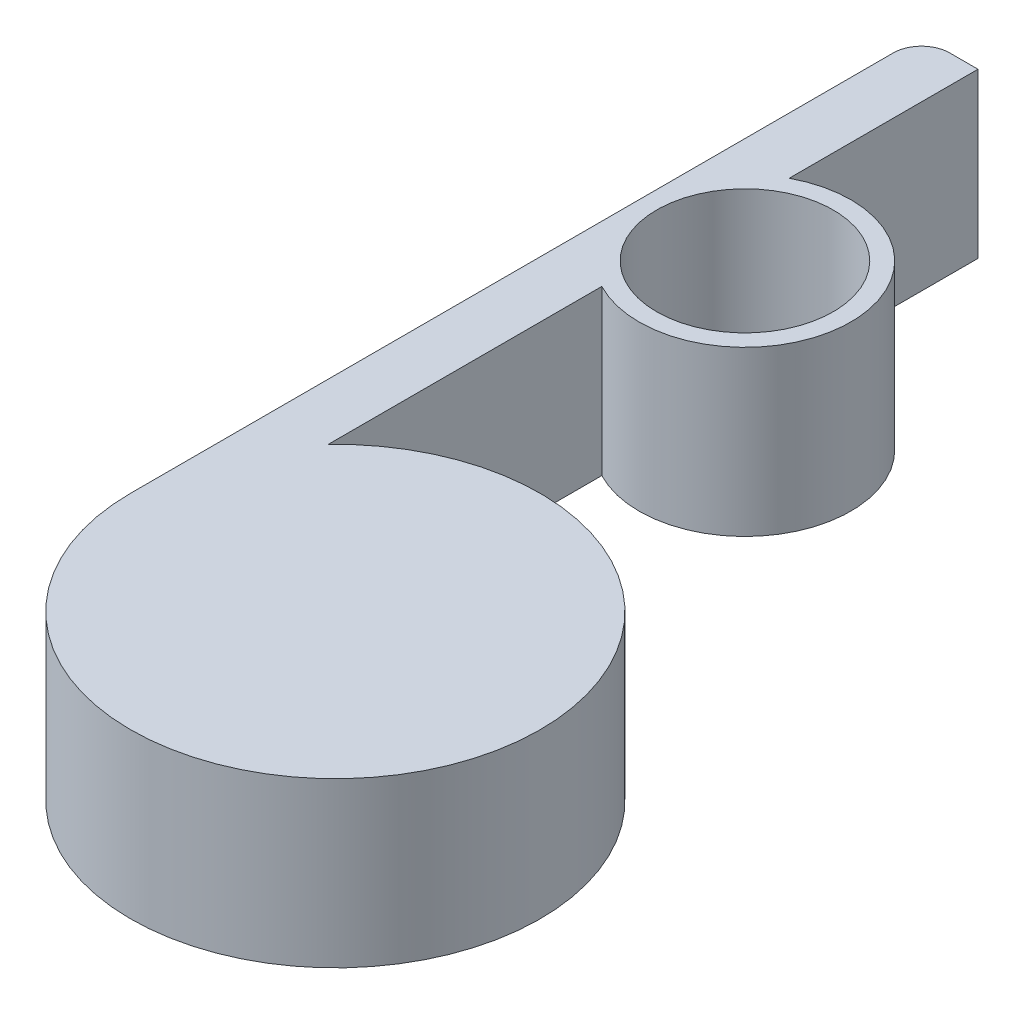
SolidWorks part; units mm, degrees
ref_plane "Front Plane" through (0, 0, 0) normal (0, 0, 1) x (1, 0, 0)
ref_plane "Top Plane" through (0, 0, 0) normal (0, 1, 0) x (1, 0, 0)
ref_plane "Right Plane" through (0, 0, 0) normal (1, 0, 0) x (0, 0, -1)
sketch "Sketch1" plane through (0, 0, 0) normal (0, 1, 0) x (1, 0, 0)
  line L0 (-3.75, 0) -> (-3.75, 10)
  line L1 (-3.75, 10) -> (-1.75, 10)
  line L2 (-1.75, 10) -> (-1.75, 3.3166)
  line L3 (-3.75, 0) -> (-3.75, -18)
  line L4 (-3.75, -18) -> (-1.75, -18)
  line L5 (-1.75, -18) -> (-1.75, -3.3166)
  line L6 (0, 0) -> (0, -18)
  line L7 (0, -18) -> (3.5, -18)
  line L8 (0, 0) -> (3.5, -18) construction
  line L9 (10.6167, -16.6162) -> (3.5, -18) construction
  circle A0 centre (0, 0) radius 3.125
  circle A1 centre (0, 0) radius 3.75
  circle A3 centre (3.5, -18) radius 7.25
  dimension "D1" = 10
  dimension "D4" = 6.25
  dimension "D5" = 7.5
  dimension "D6" = 3.5
  dimension "D2" = 18
  dimension "D3" = 2
extrude "Boss-Extrude1" add sketch "Sketch1" along normal blind 5.8 contours A1 L2 L1 L0 | A1 A0 | A3 L5 A1 L3 | L4 A3 L5 | L5 A3 L4
fillet "Fillet1" radius 1 1 edges at (-3.75, 2.9, -10)
